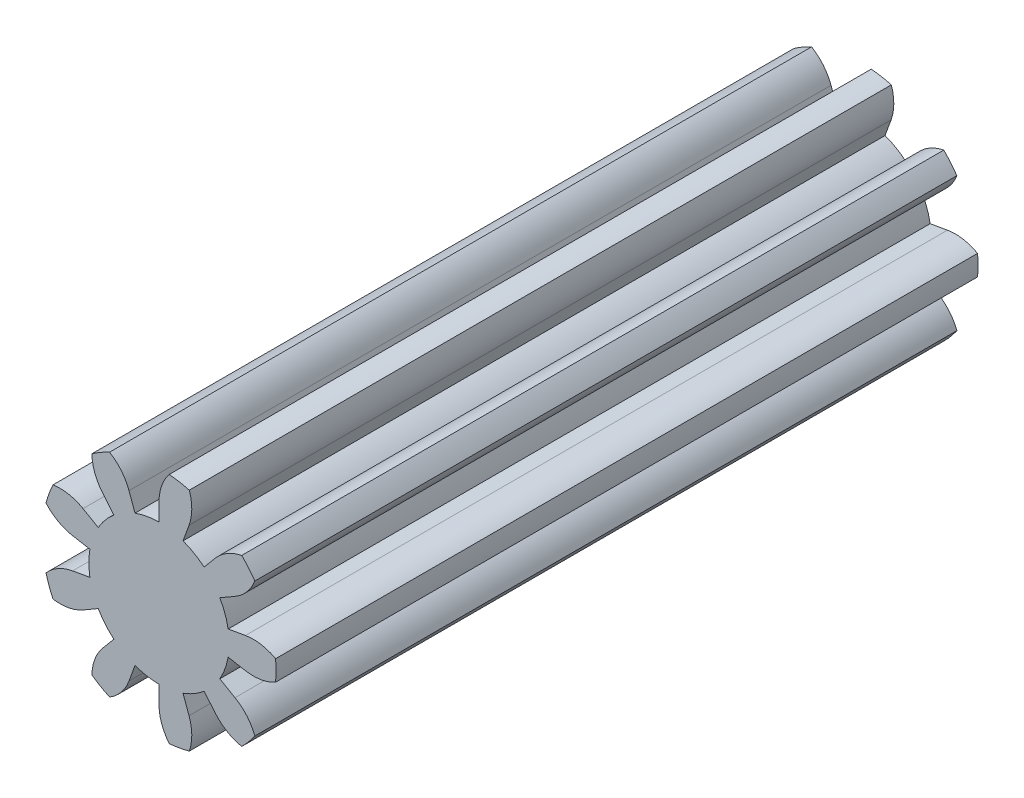
SolidWorks part; units mm, degrees
ref_plane "Front Plane" through (0, 0, 0) normal (0, 0, 1) x (1, 0, 0)
ref_plane "Top Plane" through (0, 0, 0) normal (0, 1, 0) x (1, 0, 0)
ref_plane "Right Plane" through (0, 0, 0) normal (1, 0, 0) x (0, 0, -1)
sketch "Sketch1" plane through (0, 0, 0) normal (0, 0, 1) x (1, 0, 0)
  line L0 (0, 0) -> (1, 0) construction
  line L1 (1, 0) -> (0, 0) construction
  line L2 (0, 0) -> (0.5638, 0.2052) construction
  line L3 (0, 0) -> (0.9848, 0.1736) construction
  line L4 (0, 0) -> (0.9962, 0.0872) construction
  line L5 (0.5909, 0.1042) -> (0.7386, 0.1302)
  line L6 (0.5909, -0.1042) -> (0.7386, -0.1302)
  line L7 (0.5196, -0.3) -> (0.6495, -0.375)
  line L8 (0.3857, -0.4596) -> (0.4821, -0.5745)
  line L9 (0.2052, -0.5638) -> (0.2565, -0.7048)
  line L10 (0, -0.6) -> (0, -0.75)
  line L11 (-0.2052, -0.5638) -> (-0.2565, -0.7048)
  line L12 (-0.3857, -0.4596) -> (-0.4821, -0.5745)
  line L13 (-0.5196, -0.3) -> (-0.6495, -0.375)
  line L14 (-0.5909, -0.1042) -> (-0.7386, -0.1302)
  line L15 (-0.5909, 0.1042) -> (-0.7386, 0.1302)
  line L16 (-0.5196, 0.3) -> (-0.6495, 0.375)
  line L17 (-0.3857, 0.4596) -> (-0.4821, 0.5745)
  line L18 (-0.2052, 0.5638) -> (-0.2565, 0.7048)
  line L19 (0, 0.6) -> (0, 0.75)
  line L20 (0.2052, 0.5638) -> (0.2565, 0.7048)
  line L21 (0.3857, 0.4596) -> (0.4821, 0.5745)
  line L22 (0.5196, 0.3) -> (0.6495, 0.375)
  circle A0 centre (0, 0) radius 1 construction
  circle A1 centre (0, 0) radius 0.75 construction
  circle A2 centre (0, 0) radius 0.6 construction
  arc A3 (0.5638, 0.2052) -> (0.5909, 0.1042) centre (0, 0) cw
  arc A4 (0.7386, 0.1302) -> (0.9962, 0.0872) centre (0.8066, -0.2551) cw
  arc A5 (0.9962, -0.0872) -> (0.9962, 0.0872) centre (0, 0) ccw
  arc A6 (0.7386, -0.1302) -> (0.9962, -0.0872) centre (0.8066, 0.2551) ccw
  arc A7 (0.5638, -0.2052) -> (0.5909, -0.1042) centre (0, 0) ccw
  arc A8 (0.5638, -0.2052) -> (0.5196, -0.3) centre (0, 0) cw
  arc A9 (0.6495, -0.375) -> (0.8192, -0.5736) centre (0.4539, -0.7139) cw
  arc A10 (0.7071, -0.7071) -> (0.8192, -0.5736) centre (0, 0) ccw
  arc A11 (0.4821, -0.5745) -> (0.7071, -0.7071) centre (0.7818, -0.323) ccw
  arc A12 (0.3, -0.5196) -> (0.3857, -0.4596) centre (0, 0) ccw
  arc A13 (0.3, -0.5196) -> (0.2052, -0.5638) centre (0, 0) cw
  arc A14 (0.2565, -0.7048) -> (0.2588, -0.9659) centre (-0.1112, -0.8386) cw
  arc A15 (0.0872, -0.9962) -> (0.2588, -0.9659) centre (0, 0) ccw
  arc A16 (0, -0.75) -> (0.0872, -0.9962) centre (0.3913, -0.75) ccw
  arc A17 (-0.1042, -0.5909) -> (0, -0.6) centre (0, 0) ccw
  arc A18 (-0.1042, -0.5909) -> (-0.2052, -0.5638) centre (0, 0) cw
  arc A19 (-0.2565, -0.7048) -> (-0.4226, -0.9063) centre (-0.6242, -0.5709) cw
  arc A20 (-0.5736, -0.8192) -> (-0.4226, -0.9063) centre (0, 0) ccw
  arc A21 (-0.4821, -0.5745) -> (-0.5736, -0.8192) centre (-0.1823, -0.8261) ccw
  arc A22 (-0.4596, -0.3857) -> (-0.3857, -0.4596) centre (0, 0) ccw
  arc A23 (-0.4596, -0.3857) -> (-0.5196, -0.3) centre (0, 0) cw
  arc A24 (-0.6495, -0.375) -> (-0.9063, -0.4226) centre (-0.8452, -0.0361) cw
  arc A25 (-0.9659, -0.2588) -> (-0.9063, -0.4226) centre (0, 0) ccw
  arc A26 (-0.7386, -0.1302) -> (-0.9659, -0.2588) centre (-0.6707, -0.5156) ccw
  arc A27 (-0.6, 0) -> (-0.5909, -0.1042) centre (0, 0) ccw
  arc A28 (-0.6, 0) -> (-0.5909, 0.1042) centre (0, 0) cw
  arc A29 (-0.7386, 0.1302) -> (-0.9659, 0.2588) centre (-0.6707, 0.5156) cw
  arc A30 (-0.9063, 0.4226) -> (-0.9659, 0.2588) centre (0, 0) ccw
  arc A31 (-0.6495, 0.375) -> (-0.9063, 0.4226) centre (-0.8452, 0.0361) ccw
  arc A32 (-0.4596, 0.3857) -> (-0.5196, 0.3) centre (0, 0) ccw
  arc A33 (-0.4596, 0.3857) -> (-0.3857, 0.4596) centre (0, 0) cw
  arc A34 (-0.4821, 0.5745) -> (-0.5736, 0.8192) centre (-0.1823, 0.8261) cw
  arc A35 (-0.4226, 0.9063) -> (-0.5736, 0.8192) centre (0, 0) ccw
  arc A36 (-0.2565, 0.7048) -> (-0.4226, 0.9063) centre (-0.6242, 0.5709) ccw
  arc A37 (-0.1042, 0.5909) -> (-0.2052, 0.5638) centre (0, 0) ccw
  arc A38 (-0.1042, 0.5909) -> (0, 0.6) centre (0, 0) cw
  arc A39 (0, 0.75) -> (0.0872, 0.9962) centre (0.3913, 0.75) cw
  arc A40 (0.2588, 0.9659) -> (0.0872, 0.9962) centre (0, 0) ccw
  arc A41 (0.2565, 0.7048) -> (0.2588, 0.9659) centre (-0.1112, 0.8386) ccw
  arc A42 (0.3, 0.5196) -> (0.2052, 0.5638) centre (0, 0) ccw
  arc A43 (0.3, 0.5196) -> (0.3857, 0.4596) centre (0, 0) cw
  arc A44 (0.4821, 0.5745) -> (0.7071, 0.7071) centre (0.7818, 0.323) cw
  arc A45 (0.8192, 0.5736) -> (0.7071, 0.7071) centre (0, 0) ccw
  arc A46 (0.6495, 0.375) -> (0.8192, 0.5736) centre (0.4539, 0.7139) ccw
  arc A47 (0.5638, 0.2052) -> (0.5196, 0.3) centre (0, 0) ccw
  point P101 (0, 0)
  dimension "D1" = 2
  dimension "D2" = 0.4
  dimension "D3" = 1.5
  dimension "D4" = 20
  dimension "D5" = 10
  dimension "D6" = 5
extrude "Boss-Extrude1" add sketch "Sketch1" along normal blind 6
